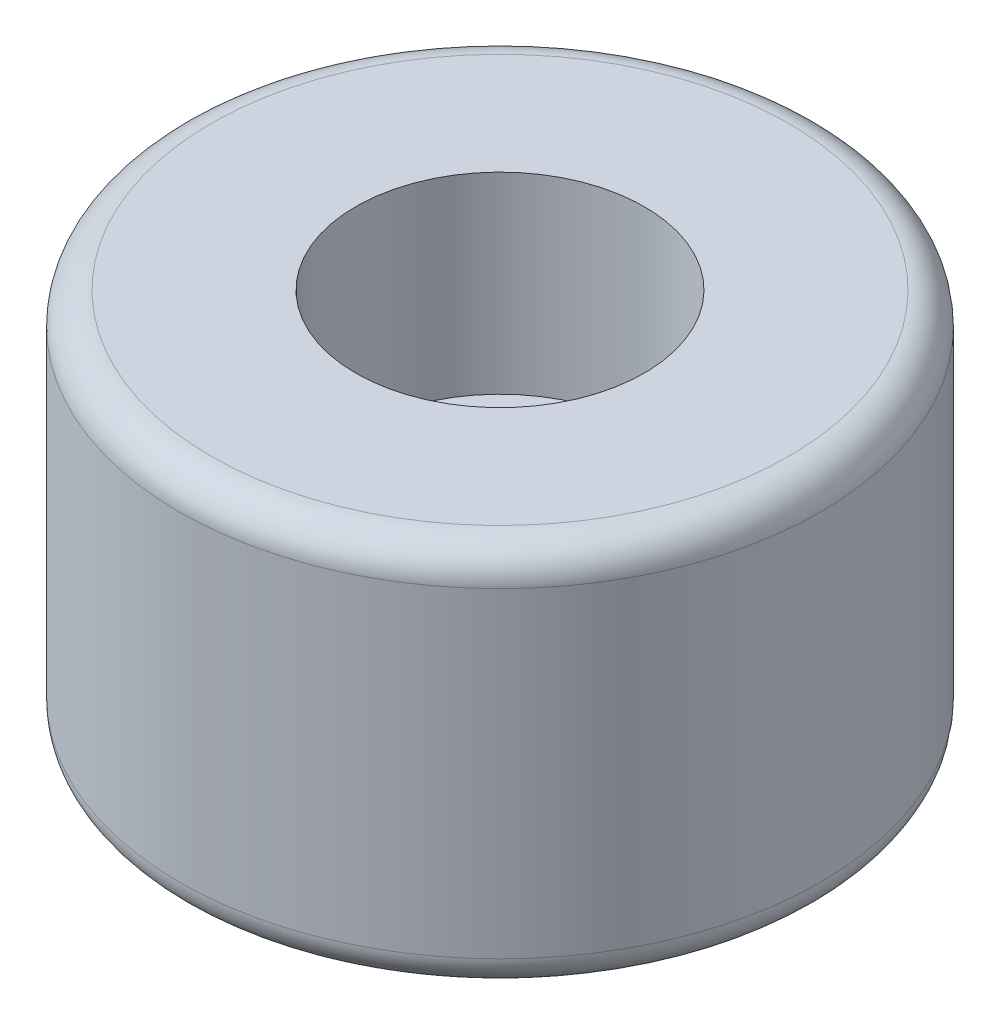
SolidWorks part; units mm, degrees
ref_plane "Front" through (0, 0, 0) normal (0, 0, 1) x (1, 0, 0)
ref_plane "Top" through (0, 0, 0) normal (0, 1, 0) x (1, 0, 0)
ref_plane "Right" through (0, 0, 0) normal (1, 0, 0) x (0, 0, -1)
sketch "Sketch1" plane through (0, 0, 0) normal (0, 1, 0) x (1, 0, 0)
  circle A0 centre (0, 0) radius 31.75
  dimension "D1" = 63.5
extrude "Boss-Extrude1" add sketch "Sketch1" along normal blind 38.1
fillet "Fillet1" radius 3.175 2 edges at (0, 0, 31.75) (0, 38.1, 31.75)
sketch "Sketch2" plane through (0, 38.1, 0) normal (0, 1, 0) x (1, 0, 0)
  circle A0 centre (0, 0) radius 14.2875
  dimension "D1" = 28.575
extrude "Cut-Extrude1" cut sketch "Sketch2" against normal blind 19.05
sketch "Sketch3" plane through (0, 19.05, 0) normal (0, 1, 0) x (1, 0, 0)
  circle A0 centre (0, 0) radius 4.7625
  dimension "D1" = 9.525
extrude "Cut-Extrude2" cut sketch "Sketch3" against normal blind 3.175
sketch "Sketch4" plane through (0, 15.875, 0) normal (0, 1, 0) x (1, 0, 0)
  circle A0 centre (0, 0) radius 3.175
  dimension "D1" = 6.35
extrude "Cut-Extrude3" cut sketch "Sketch4" against normal through all
sketch "Sketch5" plane through (0, 0, 0) normal (0, -1, 0) x (1, 0, 0)
  circle A0 centre (0, 0) radius 14.2875
  dimension "D1" = 28.575
extrude "Cut-Extrude4" cut sketch "Sketch5" against normal blind 15.875
sketch "Sketch6" plane through (0, 15.875, 0) normal (0, -1, 0) x (-1, 0, 0)
  line L0 (-14.2875, 0) -> (14.2875, 0) construction
  line L1 (0, 4.7625) -> (0, -4.7625) construction
  line L2 (-6.2708, -1) -> (-9.525, -1)
  line L3 (6.2708, 1) -> (9.525, 1)
  line L5 (6.2708, -1) -> (9.525, -1)
  line L6 (-6.2708, 1) -> (-9.525, 1)
  arc A0 (-6.2708, -1) -> (-2.4128, -5.8737) centre (0, 0) ccw
  circle A1 centre (0, 0) radius 14.2875 construction
  circle A2 centre (0, 0) radius 14.2875 construction
  circle A3 centre (0, 0) radius 4.7625 construction
  arc A4 (9.525, -1) -> (9.525, 1) centre (9.525, 0) ccw
  arc A5 (-9.525, -1) -> (-9.525, 1) centre (-9.525, 0) cw
  arc A6 (6.2708, 1) -> (2.4128, 5.8738) centre (0, 0) ccw
  arc A7 (-2.4128, -5.8737) -> (2.4128, -5.8738) centre (0, -7.9375) ccw
  arc A9 (-2.4128, 5.8737) -> (2.4128, 5.8738) centre (0, 7.9375) cw
  arc A11 (-2.4128, 5.8737) -> (-6.2708, 1) centre (0, 0) ccw
  arc A12 (2.4128, -5.8738) -> (6.2708, -1) centre (0, 0) ccw
  dimension "D1" = 12.7
  dimension "D2" = 2
  dimension "D4" = 6.35
  dimension "D5" = 15.875
  dimension "D3" = 19.05
extrude "Boss-Extrude2" add sketch "Sketch6" along normal blind 9.525
draft "Draft2" type of draft neutral plane draft angle 3 faces to draft 12 face at (10.025, 11.1125, 0) face at (4.6603, 11.1125, 3.689) face at (7.8979, 11.1125, 1) face at (7.8979, 11.1125, -1) face at (4.6603, 11.1125, -3.689) face at (0, 11.1125, -8.4931) face at (-7.8979, 11.1125, 1) face at (-7.8979, 11.1125, -1) face at (-10.025, 11.1125, 0) face at (-4.6603, 11.1125, -3.689) face at (-4.6603, 11.1125, 3.689) face at (0, 11.1125, 8.4931) neutral plane through (0, 6.35, 0) neutral plane normal (0, -1, 0) parameters "D1"=3
sketch "Sketch7" plane through (0, 6.35, 0) normal (0, -1, 0) x (-1, 0, 0)
  line L0 (-9.525, 0) -> (9.525, 0) construction
  line L1 (9.525, 0) -> (9.9857, -0.8875) construction
  circle A0 centre (0, 7.9375) radius 1.5875
  arc A1 (9.525, -1) -> (9.525, 1) centre (9.525, 0) ccw construction
  circle A2 centre (0, -7.9375) radius 1.5875
  dimension "D1" = 3.175
extrude "Cut-Extrude5" cut sketch "Sketch7" against normal through all
